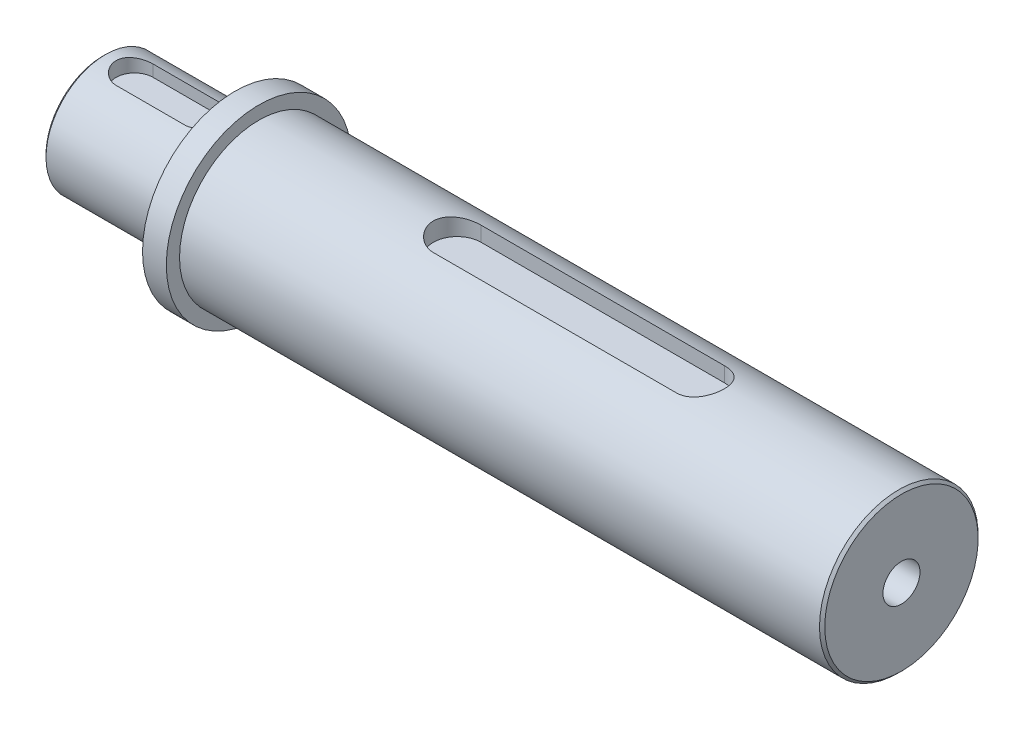
SolidWorks part; units mm, degrees
material "AISI 304"
ref_plane "Спереди" through (0, 0, 0) normal (0, 0, 1) x (1, 0, 0)
ref_plane "Сверху" through (0, 0, 0) normal (0, 1, 0) x (1, 0, 0)
ref_plane "Справа" through (0, 0, 0) normal (1, 0, 0) x (0, 0, -1)
other "Configuration Table"
sketch "Эскиз1" plane through (0, 0, 0) normal (0, 0, 1) x (1, 0, 0)
  line L0 (-233.4884, 0) -> (249.3023, 0) construction
  line L1 (-59, 0) -> (-59, 22.5)
  line L2 (-59, 22.5) -> (-9, 22.5)
  line L3 (-9, 22.5) -> (-9, 35)
  line L4 (-9, 35) -> (0, 35)
  line L5 (0, 35) -> (0, 30)
  line L6 (0, 30) -> (243, 30)
  line L7 (243, 30) -> (243, 0)
  line L8 (243, 0) -> (-59, 0)
  dimension "D1" = 50
  dimension "D2" = 45
  dimension "D3" = 60
  dimension "D4" = 70
  dimension "D5" = 9
  dimension "D6" = 243
revolve "Повернуть1" add sketch "Эскиз1" angle 360 about L0
chamfer "Фаска1" distance 1 angle 45 2 edges at (243, 0, 30) (-59, 0, 22.5)
hole_wizard "Отверстие обработанное метчиком M161" positions "Эскиз2" profile "Эскиз3" tap size "M16" standard "DIN"
sketch "Эскиз2" plane through (243, 0, 0) normal (1, 0, 0) x (0, 0, -1)
  point P0 (0, 0)
sketch "Эскиз3" plane through (243, 0, 0) normal (0, 1, 0) x (0, 0, -1)
  line L0 (0, 0) -> (0, 45)
  line L1 (0, 45) -> (7, 40.794)
  line L2 (7, 40.794) -> (7, 0)
  line L5 (7, 0) -> (0, 0)
  line L10 (0, 45) -> (-7, 40.794) construction
  line L11 (0, -6.35) -> (0, 107.95) construction
  dimension "Диаметр сверла" = 14
  dimension "Глубина сверла" = 45
  dimension "Угол заточки сверла" = 118
cosmetic thread "Отверстие резьбы1" parameters "D1"=32, "D2"=16
ref_plane "Плоскость1" through (0, 30, 0) normal (0, 1, 0) x (1, 0, 0)
sketch "Эскиз4" plane through (0, 30, 0) normal (0, 1, 0) x (1, 0, 0)
  line L0 (167, 0) -> (75, 0) construction
  line L1 (167, -9) -> (75, -9)
  line L2 (167, 9) -> (75, 9)
  line L4 (243, -29) -> (243, 29) construction
  arc A0 (167, -9) -> (167, 9) centre (167, 0) ccw
  arc A1 (75, 9) -> (75, -9) centre (75, 0) ccw
  point P3 (121, 0)
  dimension "D1" = 122
  dimension "D2" = 92
extrude "Вырез-Вытянуть1" cut sketch "Эскиз4" against normal blind 7
ref_plane "Плоскость2" through (0, 22.5, 0) normal (0, 1, 0) x (1, 0, 0)
sketch "Эскиз5" plane through (0, 22.5, 0) normal (0, 1, 0) x (1, 0, 0)
  line L0 (-47, 0) -> (-21, 0) construction
  line L1 (-50, 0) -> (50, 0) construction
  line L2 (-47, 7) -> (-21, 7)
  line L3 (-47, -7) -> (-21, -7)
  line L5 (-59, 21.5) -> (-59, -21.5) construction
  arc A0 (-47, 7) -> (-47, -7) centre (-47, 0) ccw
  arc A1 (-21, -7) -> (-21, 7) centre (-21, 0) ccw
  point P5 (-34, 0)
  point P12 (-54, 0)
  point P13 (-14, 0)
  dimension "D1" = 7
  dimension "D2" = 40
  dimension "D3" = 5
extrude "Вырез-Вытянуть2" cut sketch "Эскиз5" against normal blind 5.5
